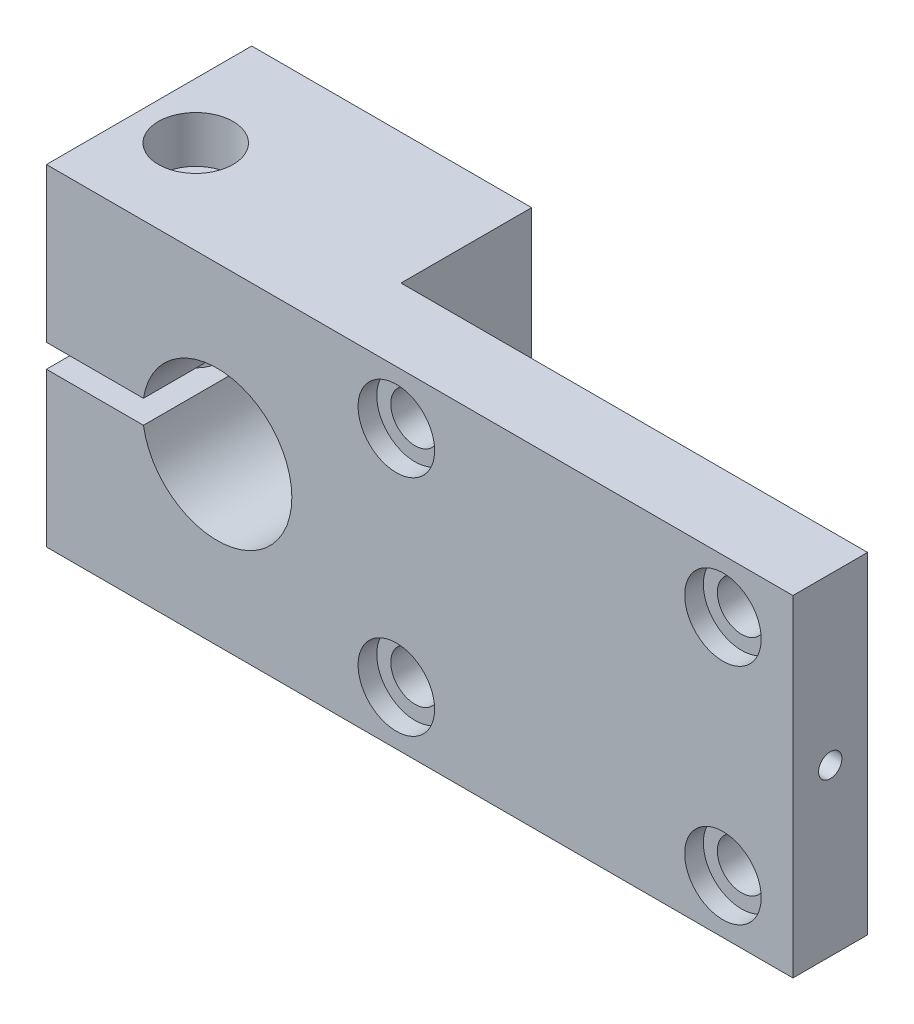
SolidWorks part; units mm, degrees
ref_plane "Plan de face" through (0, 0, 0) normal (0, 0, 1) x (1, 0, 0)
ref_plane "Plan de dessus" through (0, 0, 0) normal (0, 1, 0) x (1, 0, 0)
ref_plane "Plan de droite" through (0, 0, 0) normal (1, 0, 0) x (0, 0, -1)
sketch "Esquisse1" plane through (0, 0, 0) normal (0, 0, 1) x (1, 0, 0)
  line L0 (-18.3, 1.25) -> (-7.9017, 1.25)
  line L1 (-7.9017, -1.25) -> (-18.3, -1.25)
  line L2 (-18.3, -1.25) -> (-18.3, -15.75)
  line L3 (-18.3, -15.75) -> (61.7, -15.75)
  line L4 (61.7, -15.75) -> (61.7, 15.75)
  line L5 (61.7, 15.75) -> (-18.3, 15.75)
  line L6 (-18.3, 15.75) -> (-18.3, 1.25)
  line L7 (0, 0) -> (-41.9762, 0) construction
  arc A0 (-7.9017, -1.25) -> (-7.9017, 1.25) centre (0, 0) ccw
  circle A1 centre (19.2, -12) radius 2.1
  circle A3 centre (54.2, -12) radius 2.1
  circle A4 centre (54.2, 12) radius 2.1
  circle A5 centre (19.2, 12) radius 2.1
  dimension "D4" = 8
  dimension "D5" = 24
  dimension "D6" = 35
  dimension "D7" = 7.5
  dimension "D8" = 24
  dimension "D9" = 35
  dimension "D10" = 3.75
  dimension "D11" = 3.75
  dimension "D12" = 3.75
  dimension "D13" = 14.5
  dimension "D16" = 4.2
  dimension "D17" = 4.2
  dimension "D18" = 4.2
  dimension "D19" = 4.2
  dimension "D1" = 80
  dimension "D2" = 31.5
  dimension "D3" = 2.5
  dimension "D14" = 10.3983
  dimension "D15" = 1.25
extrude "Boss.-Extru.1" add sketch "Esquisse1" along normal blind 22
sketch "Esquisse2" plane through (0, 15.75, 0) normal (0, 1, 0) x (1, 0, 0)
  line L0 (61.7, 0) -> (-18.3, 0) construction
  line L1 (64.2438, 3.4472) -> (11.7, 3.4472)
  line L2 (64.2438, 3.4472) -> (64.2438, -14)
  line L3 (64.2438, -14) -> (11.7, -14)
  line L4 (11.7, 3.4472) -> (11.7, -14)
  line L5 (61.7, -22) -> (61.7, 0) construction
  dimension "D1" = 14
  dimension "D2" = 50
extrude "Enlèv. mat.-Extru.1" cut sketch "Esquisse2" against normal blind 42
sketch "Esquisse3" plane through (0, 0, 22) normal (0, 0, 1) x (1, 0, 0)
  line L0 (61.7, 0) -> (0, 0) construction
  line L1 (61.7, -15.75) -> (61.7, 15.75) construction
  circle A4 centre (19.2, -12) radius 2.1 construction
  circle A5 centre (54.2, -12) radius 2.1 construction
  circle A6 centre (54.2, 12) radius 2.6 construction
  circle A7 centre (19.2, 12) radius 2.1 construction
  circle A8 centre (19.2, -12) radius 3.1
  circle A9 centre (54.2, -12) radius 3.1
  circle A10 centre (54.2, 12) radius 3.6
  circle A11 centre (19.2, 12) radius 3.1
  dimension "D2" = 12
  dimension "D9" = 5.2
  dimension "D3" = 12
  dimension "D4" = 12
  dimension "D5" = 12
  dimension "D6" = 35
  dimension "D7" = 7.5
  dimension "D8" = 7.5
  dimension "D1" = 1
extrude "Enlèv. mat.-Extru.2" cut sketch "Esquisse3" against normal blind 2
hole_wizard "Dégagement M51" positions "Esquisse4" profile "Esquisse5" hole size "M5" standard "Ansi Metric"
sketch "Esquisse4" plane through (0, 15.75, 0) normal (0, 1, 0) x (1, 0, 0)
  line L0 (61.7, -22) -> (-18.3, -22) construction
  line L1 (-18.3, -22) -> (-18.3, 0) construction
  point P0 (-12.3, -12)
  dimension "D1" = 10
  dimension "D2" = 6
sketch "Esquisse5" plane through (-12.3, 15.75, 12) normal (1, 0, 0) x (0, 0, 1)
  line L0 (0, 0) -> (0, 35.5923)
  line L1 (0, 35.5923) -> (2.65, 34)
  line L2 (2.65, 34) -> (2.65, 0)
  line L5 (2.65, 0) -> (0, 0)
  line L10 (0, 35.5923) -> (-2.65, 34) construction
  line L11 (0, -6.35) -> (0, 107.95) construction
  dimension "Diamètre du perçage" = 5.3
  dimension "Profondeur du perçage" = 34
  dimension "Angle de pointe" = 118
sketch "Esquisse6" plane through (0, 15.75, 0) normal (0, 1, 0) x (1, 0, 0)
  circle A0 centre (-12.3, -12) radius 4
  dimension "D1" = 8
extrude "Enlèv. mat.-Extru.3" cut sketch "Esquisse6" against normal blind 3
sketch "Esquisse7" plane through (0, -15.75, 0) normal (0, -1, 0) x (1, 0, 0)
  line L1 (-12.3, 16.6188) -> (-16.3, 14.3094)
  line L2 (-16.3, 14.3094) -> (-16.3, 9.6906)
  line L3 (-16.3, 9.6906) -> (-12.3, 7.3812)
  line L4 (-12.3, 7.3812) -> (-8.3, 9.6906)
  line L5 (-8.3, 9.6906) -> (-8.3, 14.3094)
  line L6 (-8.3, 14.3094) -> (-12.3, 16.6188)
  circle A0 centre (-12.3, 12) radius 4 construction
  dimension "D1" = 8
extrude "Enlèv. mat.-Extru.4" cut sketch "Esquisse7" against normal blind 8
sketch "Esquisse8" plane through (61.7, 0, 0) normal (1, 0, 0) x (0, 0, -1)
  line L0 (-22, -15.75) -> (-14, -15.75) construction
  line L1 (-22, -15.75) -> (-22, 15.75) construction
  circle A0 centre (-18, 0) radius 1.25
  dimension "D1" = 15.75
  dimension "D2" = 2.5
  dimension "D3" = 4
extrude "Enlèv. mat.-Extru.5" cut sketch "Esquisse8" against normal blind 5
sketch "Esquisse9" plane through (0, 15.75, 0) normal (0, 1, 0) x (1, 0, 0)
  line L6 (61.7, -22) -> (61.7, -14)
  line L7 (61.7, -14) -> (11.7, -14)
  line L8 (11.7, -14) -> (11.7, 0)
  line L9 (11.7, 0) -> (-18.3, 0)
  line L10 (-18.3, 0) -> (-18.3, -22)
  line L11 (-18.3, -22) -> (61.7, -22)
  line L12 (61.7, -22) -> (61.7, -14)
  line L13 (61.7, -14) -> (11.7, -14)
  line L14 (11.7, -14) -> (11.7, 0)
  line L15 (11.7, 0) -> (-18.3, 0)
  line L16 (-18.3, 0) -> (-18.3, -22)
  line L17 (-18.3, -22) -> (61.7, -22)
  circle A0 centre (-12.3, -12) radius 4 construction
  circle A1 centre (-12.3, -12) radius 4
  dimension "D1" = 0
extrude "Boss.-Extru.2" add sketch "Esquisse9" along normal blind 2
sketch "Esquisse10" plane through (0, -15.75, 0) normal (0, -1, 0) x (1, 0, 0)
  line L0 (-12.3, 16.6188) -> (-16.3, 14.3094) construction
  line L1 (-16.3, 14.3094) -> (-16.3, 9.6906) construction
  line L2 (-16.3, 9.6906) -> (-12.3, 7.3812) construction
  line L3 (-12.3, 7.3812) -> (-8.3, 9.6906) construction
  line L4 (-8.3, 9.6906) -> (-8.3, 14.3094) construction
  line L5 (-8.3, 14.3094) -> (-12.3, 16.6188) construction
  line L6 (11.7, 0) -> (11.7, 14)
  line L7 (11.7, 14) -> (61.7, 14)
  line L8 (61.7, 14) -> (61.7, 22)
  line L9 (61.7, 22) -> (-18.3, 22)
  line L10 (-18.3, 22) -> (-18.3, 0)
  line L11 (-18.3, 0) -> (11.7, 0)
  line L12 (11.7, 0) -> (11.7, 14)
  line L13 (11.7, 14) -> (61.7, 14)
  line L14 (61.7, 14) -> (61.7, 22)
  line L15 (61.7, 22) -> (-18.3, 22)
  line L16 (-18.3, 22) -> (-18.3, 0)
  line L17 (-18.3, 0) -> (11.7, 0)
  line L18 (-12.3, 16.6188) -> (-16.3, 14.3094)
  line L19 (-16.3, 14.3094) -> (-16.3, 9.6906)
  line L20 (-16.3, 9.6906) -> (-12.3, 7.3812)
  line L21 (-12.3, 7.3812) -> (-8.3, 9.6906)
  line L22 (-8.3, 9.6906) -> (-8.3, 14.3094)
  line L23 (-8.3, 14.3094) -> (-12.3, 16.6188)
  dimension "D1" = 0
extrude "Boss.-Extru.3" add sketch "Esquisse10" along normal blind 2
sketch "Esquisse11" plane through (0, 0, 20) normal (0, 0, 1) x (1, 0, 0)
  circle A0 centre (54.2, 12) radius 2.6
  circle A1 centre (54.2, -12) radius 2.6
  circle A2 centre (19.2, -12) radius 2.6
  circle A3 centre (19.2, 12) radius 2.6
  dimension "D1" = 5.2
  dimension "D2" = 5.2
  dimension "D3" = 5.2
  dimension "D4" = 5.2
extrude "Enlèv. mat.-Extru.6" cut sketch "Esquisse11" against normal blind 10
sketch "Esquisse12" plane through (0, 0, 22) normal (0, 0, 1) x (1, 0, 0)
  circle A0 centre (54.2, -12) radius 3.1 construction
  circle A1 centre (19.2, -12) radius 3.1 construction
  circle A2 centre (19.2, 12) radius 3.1 construction
  circle A3 centre (54.2, -12) radius 3.1 construction
  circle A4 centre (19.2, -12) radius 3.1 construction
  circle A5 centre (19.2, 12) radius 3.1 construction
  circle A6 centre (54.2, -12) radius 4.1
  circle A7 centre (19.2, -12) radius 4.1
  circle A8 centre (19.2, 12) radius 4.1
  circle A9 centre (54.2, 12) radius 4.1
  dimension "D2" = 8.2
  dimension "D1" = 1
extrude "Enlèv. mat.-Extru.7" cut sketch "Esquisse12" against normal blind 2
